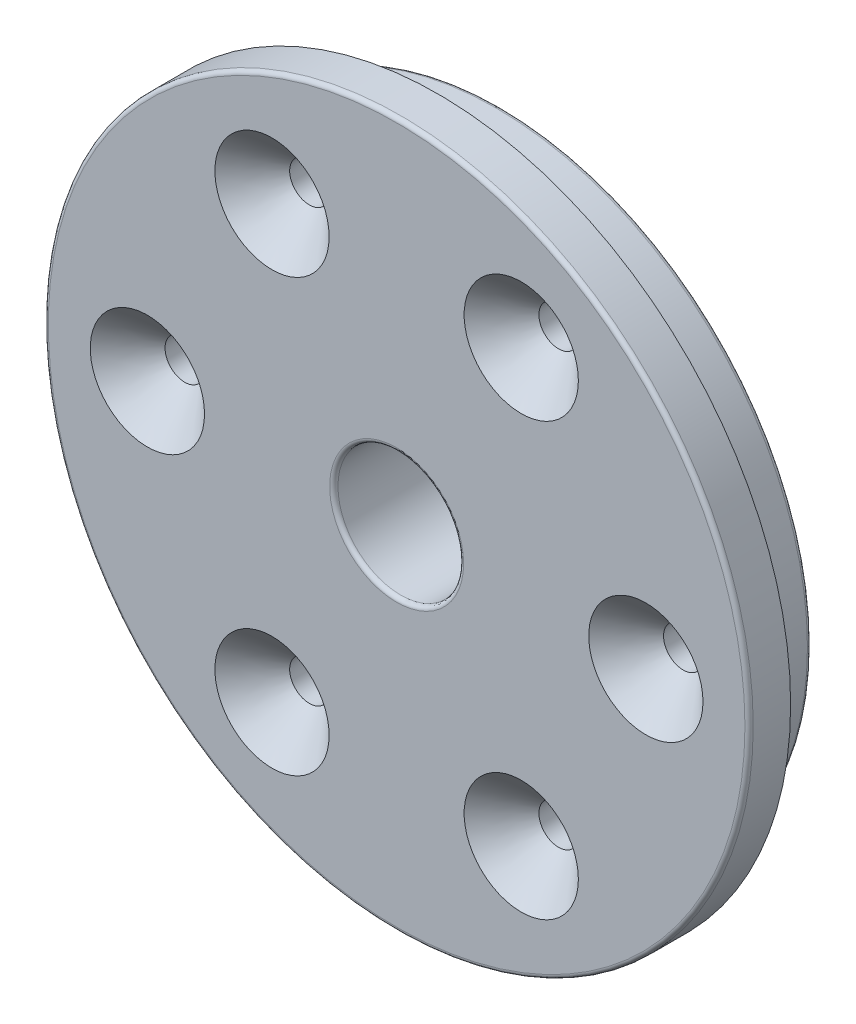
SolidWorks part; units mm, degrees
ref_plane "前视基准面" through (0, 0, 0) normal (0, 0, 1) x (1, 0, 0)
ref_plane "上视基准面" through (0, 0, 0) normal (0, 1, 0) x (1, 0, 0)
ref_plane "右视基准面" through (0, 0, 0) normal (1, 0, 0) x (0, 0, -1)
sketch "草图1" plane through (0, 0, 0) normal (0, 0, 1) x (1, 0, 0)
  circle A0 centre (0, 0) radius 16.97
  circle A7 centre (-12, 0) radius 0.95
  circle A8 centre (-6, 10.3923) radius 0.95
  circle A9 centre (6, 10.3923) radius 0.95
  circle A10 centre (12, 0) radius 0.95
  circle A11 centre (-6, -10.3923) radius 0.95
  circle A12 centre (6, -10.3923) radius 0.95
  circle A13 centre (0, 0) radius 3.025
  dimension "D1" = 6.05
  dimension "D2" = 33.94
extrude "凸台-拉伸1" add sketch "草图1" along normal blind 2
sketch "草图4" plane through (0, 0, 0) normal (0, 0, -1) x (-1, 0, 0)
  circle A0 centre (6, 10.3923) radius 0.95 construction
  circle A1 centre (0, 0) radius 14.98
  circle A2 centre (0, 0) radius 14.98
  circle A3 centre (12, 0) radius 0.95 construction
  circle A4 centre (6, -10.3923) radius 0.95 construction
  circle A5 centre (-6, -10.3923) radius 0.95 construction
  circle A6 centre (-12, 0) radius 0.95 construction
  circle A7 centre (-6, 10.3923) radius 0.95 construction
  circle A8 centre (6, 10.3923) radius 0.95
  circle A9 centre (12, 0) radius 0.95
  circle A10 centre (6, -10.3923) radius 0.95
  circle A11 centre (-6, -10.3923) radius 0.95
  circle A12 centre (-12, 0) radius 0.95
  circle A13 centre (-6, 10.3923) radius 0.95
  circle A14 centre (0, 0) radius 3.025 construction
  circle A15 centre (0, 0) radius 3.025
  dimension "D1" = 0
extrude "凸台-拉伸2" add sketch "草图4" along normal up to surface (3 mm away)
chamfer "倒角1" distance 1.8 angle 45 6 edges at (-5.05, -10.3923, 2) (-11.05, 0, 2) (-5.05, 10.3923, 2) (6.95, 10.3923, 2) (6.95, -10.3923, 2) (12.95, 0, 2)
sketch "草图5" plane through (0, 0, -3) normal (0, 0, -1) x (-1, 0, 0)
  circle A0 centre (0, 0) radius 5.025
  circle A1 centre (0, 0) radius 3.025 construction
  circle A2 centre (0, 0) radius 3.025
  dimension "D1" = 2
extrude "凸台-拉伸3" add sketch "草图5" along normal blind 5
fillet "圆角1" radius 0.2 1 edges at (-14.98, 0, 0)
fillet "圆角2" radius 0.2 5 edges at (-5.025, 0, -8) (-3.025, 0, -8) (3.025, 0, 2) (16.97, 0, 2) (0, -14.98, -3)
